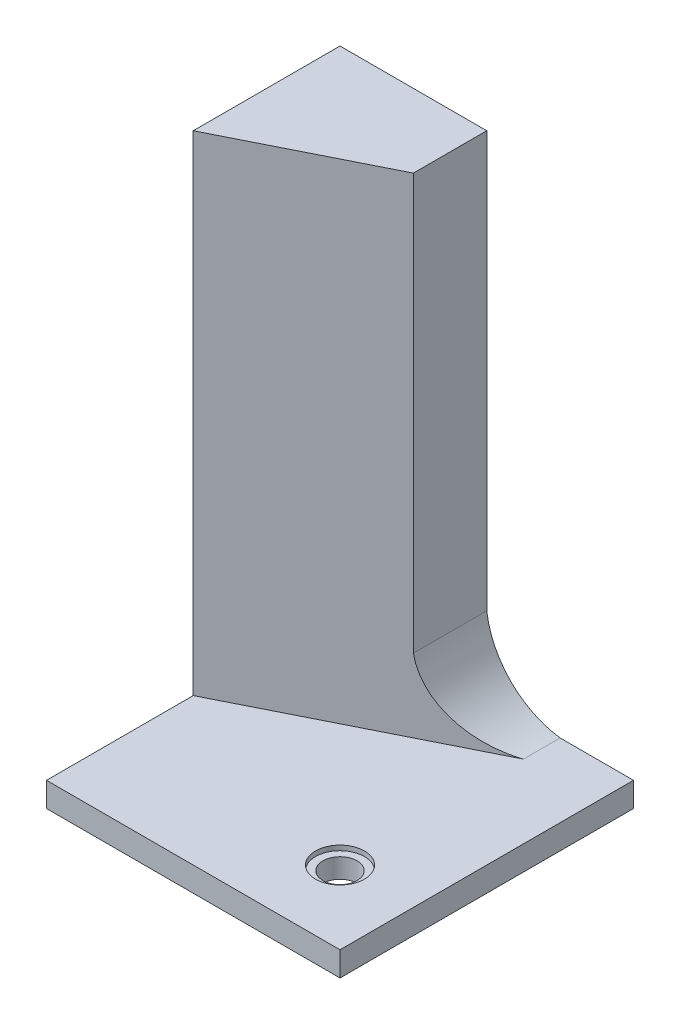
SolidWorks part; units mm, degrees
ref_plane "Front Plane" through (0, 0, 0) normal (0, 0, 1) x (1, 0, 0)
ref_plane "Top Plane" through (0, 0, 0) normal (0, 1, 0) x (1, 0, 0)
ref_plane "Right Plane" through (0, 0, 0) normal (1, 0, 0) x (0, 0, -1)
sketch "Sketch1" plane through (0, 0, 0) normal (0, 1, 0) x (1, 0, 0)
  line L1 (30, -30) -> (-30, -30)
  line L2 (30, -30) -> (30, 30)
  line L3 (30, 30) -> (-30, 30)
  line L4 (-30, -30) -> (-30, 30)
  line L5 (30, -30) -> (-30, 30) construction
  line L6 (30, 30) -> (-30, -30) construction
  point P0 (0, 0)
  dimension "D1" = 60
  dimension "D2" = 60
extrude "Boss-Extrude1" add sketch "Sketch1" along normal blind 5
sketch "Sketch2" plane through (0, 5, 0) normal (0, 1, 0) x (1, 0, 0)
  line L0 (-30, 30) -> (-30, 0)
  line L1 (-30, 0) -> (0, 15)
  line L2 (-30, 30) -> (0, 30)
  line L3 (30, 30) -> (-30, 30) construction
  line L4 (0, 30) -> (0, 15)
  dimension "D1" = 30
  dimension "D2" = 30
extrude "Boss-Extrude2" add sketch "Sketch2" along normal blind 100
sketch "Sketch3" plane through (0, 5, 0) normal (0, 1, 0) x (1, 0, 0)
  line L0 (30, 30) -> (0, 30) construction
  line L1 (0, 15) -> (15, 15)
  line L2 (0, 15) -> (0, 30)
  line L3 (0, 30) -> (15, 30)
  line L4 (15, 15) -> (15, 30)
  dimension "D1" = 15
extrude "Boss-Extrude3" add sketch "Sketch3" along normal blind 15
sketch "Sketch4" plane through (0, 0, -15) normal (0, 0, 1) x (1, 0, 0)
  line L3 (0, 20) -> (15, 20)
  line L4 (15, 20) -> (15, 5)
  arc A0 (0, 20) -> (15, 5) centre (17.1779, 22.1779) ccw
extrude "Cut-Extrude1" cut sketch "Sketch4" against normal through all
sketch "Sketch5" plane through (0, 5, 0) normal (0, 1, 0) x (1, 0, 0)
  line L0 (30, -30) -> (30, 30) construction
  line L1 (-30, -30) -> (30, -30) construction
  circle A0 centre (15, -15) radius 3.5
  dimension "D1" = 7
  dimension "D3" = 15
  dimension "D2" = 15
extrude "Cut-Extrude2" cut sketch "Sketch5" against normal through all
sketch "Sketch6" plane through (0, 5, 0) normal (0, 1, 0) x (1, 0, 0)
  circle A0 centre (15, -15) radius 5
  dimension "D1" = 10
extrude "Cut-Extrude3" cut sketch "Sketch6" against normal blind 1
sketch "Sketch7" plane through (0, 5, 0) normal (0, 1, 0) x (1, 0, 0)
  line L0 (0, 15) -> (30, 30)
  line L1 (30, 30) -> (30, 7.1196)
  line L2 (30, -30) -> (30, 30) construction
  line L3 (30, 7.1196) -> (0, 7.1196)
  line L4 (0, 7.1196) -> (0, 15)
extrude "Cut-Extrude4" cut sketch "Sketch7" along normal through all
